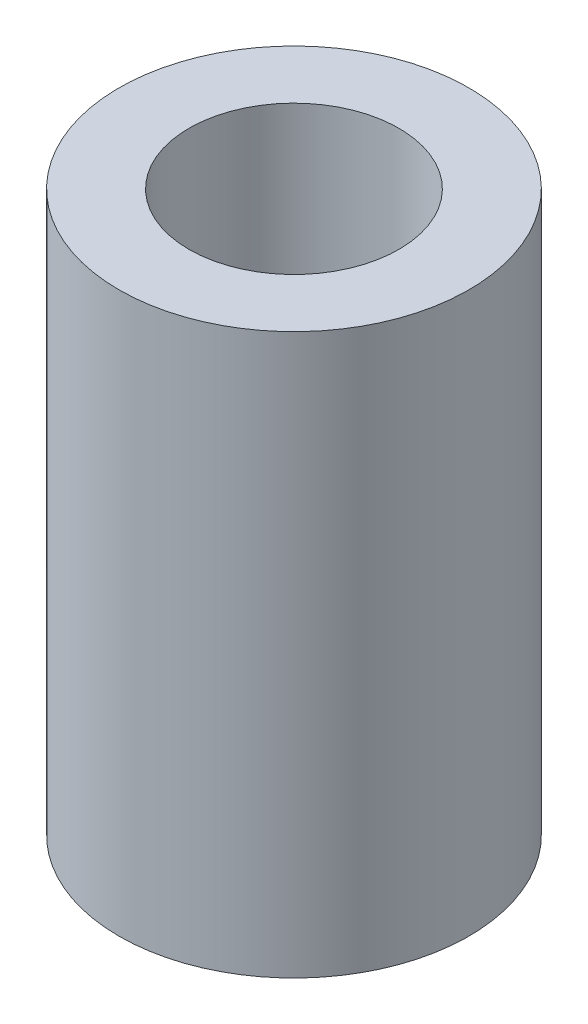
SolidWorks part; units mm, degrees
ref_plane "Front Plane" through (0, 0, 0) normal (0, 0, 1) x (1, 0, 0)
ref_plane "Top Plane" through (0, 0, 0) normal (0, 1, 0) x (1, 0, 0)
ref_plane "Right Plane" through (0, 0, 0) normal (1, 0, 0) x (0, 0, -1)
sketch "Sketch1" plane through (0, 0, 0) normal (0, 1, 0) x (1, 0, 0)
  circle A0 centre (0, 0) radius 1.5
  circle A1 centre (0, 0) radius 2.5
  dimension "D1" = 5
  dimension "D2" = 3
extrude "Boss-Extrude1" add sketch "Sketch1" along normal blind 8
